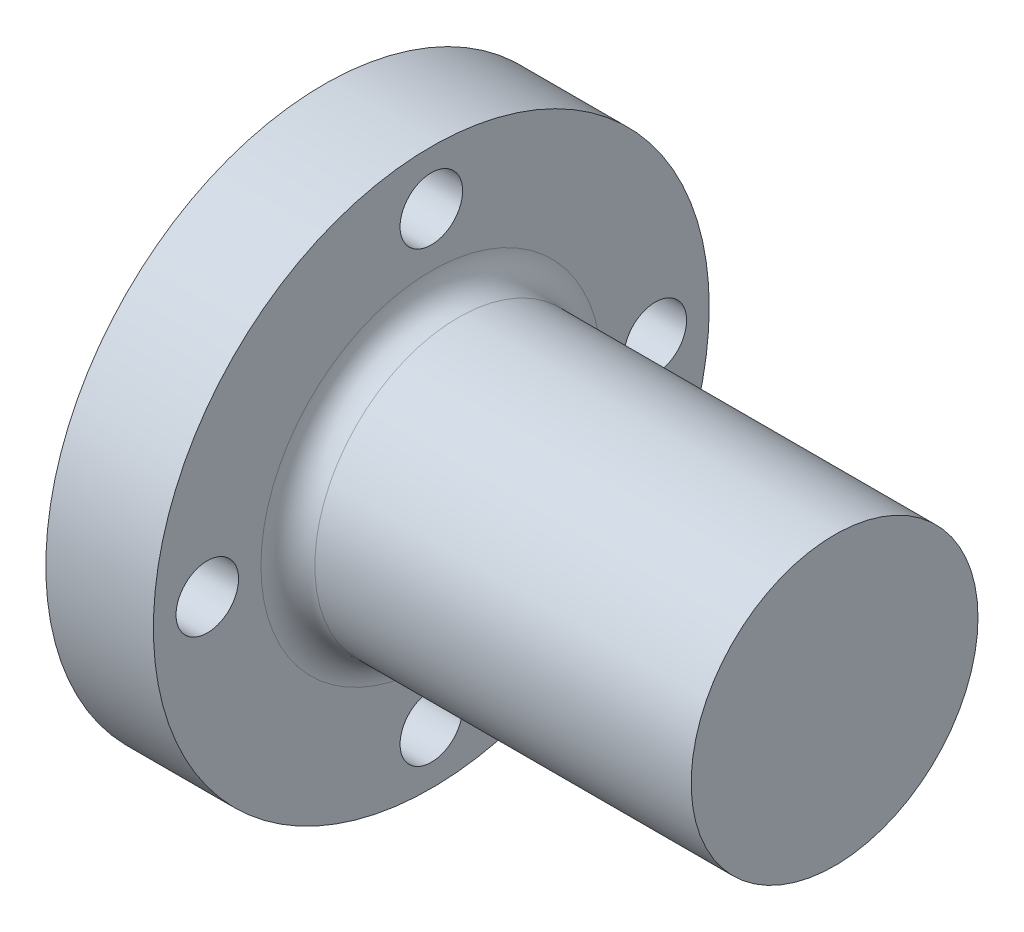
SolidWorks part; units mm, degrees
ref_plane "Front Plane" through (0, 0, 0) normal (1, 0, 0) x (0, 1, 0)
ref_plane "Top Plane" through (0, 0, 0) normal (0, 0, 1) x (0, 1, 0)
ref_plane "Right Plane" through (0, 0, 0) normal (0, 1, 0) x (-1, 0, 0)
sketch "Sketch1" plane through (0, 0, 0) normal (1, 0, 0) x (0, 1, 0)
  circle A0 centre (0, 0) radius 24.6126
extrude "Boss-Extrude1" add sketch "Sketch1" along normal blind 9.525
sketch "Sketch2" plane through (0, 0, 0) normal (1, 0, 0) x (0, 1, 0)
  circle A0 centre (0, 0) radius 12.7
extrude "Boss-Extrude2" add sketch "Sketch2" along normal blind 35.7124 from offset 9.525
sketch "Sketch3" plane through (0, 0, 0) normal (1, 0, 0) x (0, 1, 0)
  circle A0 centre (0, 0) radius 8.7122
extrude "Boss-Extrude4" add sketch "Sketch3" against normal blind 4.826
sketch "Sketch4" plane through (0, 0, 0) normal (1, 0, 0) x (0, 1, 0)
  circle A0 centre (0, 19.8374) radius 2.7686
  circle A1 centre (19.8374, 0) radius 2.7686
  circle A2 centre (0, -19.8374) radius 2.7686
  circle A3 centre (-19.8374, 0) radius 2.7686
extrude "Cut-Extrude2" cut sketch "Sketch4" along normal through all
fillet "Fillet1" radius 0.381 1 edges at (0, 0, -8.7122)
fillet "Fillet2" radius 2.3876 1 edges at (9.525, 0, -12.7)
